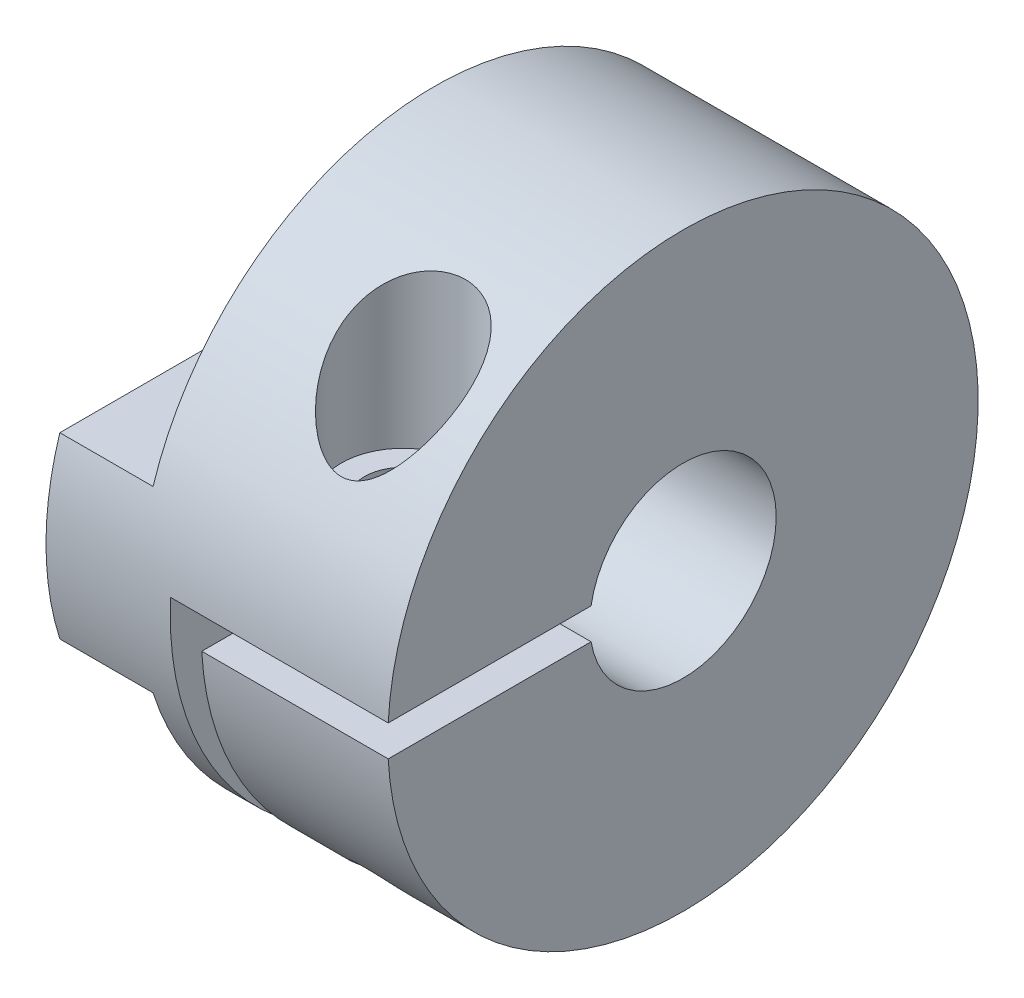
SolidWorks part; units mm, degrees
ref_plane "Plan1" through (0, 0, 0) normal (0, 0, 1) x (1, 0, 0)
ref_plane "Plan2" through (0, 0, 0) normal (0, 1, 0) x (1, 0, 0)
ref_plane "Plan3" through (0, 0, 0) normal (1, 0, 0) x (0, 0, -1)
sketch "Esquisse1" plane through (0, 0, 0) normal (0, 0, 1) x (1, 0, 0)
  line L0 (0, 0) -> (24.7291, 0) construction
  line L1 (0, 1.5) -> (0, 9.5)
  line L2 (0, 9.5) -> (11, 9.5)
  line L3 (11, 9.5) -> (11, 3)
  line L4 (11, 3) -> (4, 3)
  line L5 (4, 3) -> (4, 1.5)
  line L6 (4, 1.5) -> (0, 1.5)
  dimension "D1" = 9.5
  dimension "D2" = 3
  dimension "D3" = 11
  dimension "D4" = 1.5
  dimension "D5" = 7
revolve "Base-Révolution" add sketch "Esquisse1" angle 360 about L0
sketch "Esquisse2" plane through (0, 0, 0) normal (0, 0, 1) x (1, 0, 0)
  line L0 (-3.1407, 0) -> (12.8606, 0) construction
  line L1 (0, 0) -> (24.7291, 0) construction
  line L2 (0, 9.5) -> (0, -9.5) construction
  line L3 (0, 2.875) -> (3, 2.875)
  line L4 (0, 2.875) -> (0, 9.5)
  line L5 (0, 9.5) -> (3, 9.5)
  line L6 (3, 2.875) -> (3, 9.5)
  line L7 (11, 9.5) -> (0, 9.5) construction
  line L8 (3, -2.875) -> (3, -9.5)
  line L9 (0, -9.5) -> (3, -9.5)
  line L10 (0, -2.875) -> (0, -9.5)
  line L11 (0, -2.875) -> (3, -2.875)
  dimension "D1" = 3
  dimension "D2" = 2.875
extrude "Enlèv. mat.-Extru.1" cut sketch "Esquisse2" against normal mid plane 20
sketch "Esquisse3" plane through (0, 0, 0) normal (0, 1, 0) x (1, 0, 0)
  line L0 (11, 9.5) -> (0, 9.5) construction
  line L1 (4, -9.5) -> (5, -9.5)
  line L2 (4, -9.5) -> (4, 9.5)
  line L3 (4, 9.5) -> (5, 9.5)
  line L4 (5, -9.5) -> (5, 9.5)
  line L5 (3, 9.0545) -> (3, -9.0545) construction
  line L6 (0, -9.5) -> (11, -9.5) construction
  dimension "D1" = 1
  dimension "D2" = 1
extrude "Enlèv. mat.-Extru.2" cut sketch "Esquisse3" against normal through all
sketch "Esquisse4" plane through (11, 0, 0) normal (1, 0, 0) x (0, 0, -1)
  line L0 (0, 0) -> (-11.0166, 0) construction
  line L1 (-9.5, 0.5) -> (0, 0.5)
  line L2 (-9.5, 0.5) -> (-9.5, -0.5)
  line L3 (-9.5, -0.5) -> (0, -0.5)
  line L4 (0, 0.5) -> (0, -0.5)
  circle A0 centre (0, 0) radius 9.5 construction
  dimension "D1" = 1
extrude "Enlèv. mat.-Extru.3" cut sketch "Esquisse4" against normal blind 7
sketch "Esquisse5" plane through (0, 0, 0) normal (0, 1, 0) x (1, 0, 0)
  line L0 (11, -9.4868) -> (11, 9.5) construction
  line L1 (0, 0) -> (11.9937, 0) construction
  line L2 (0, 0) -> (24.7291, 0) construction
  circle A0 centre (8, -6) radius 1.25
  dimension "D1" = 2.5
  dimension "D2" = 3
  dimension "D3" = 6
extrude "Enlèv. mat.-Extru.4" cut sketch "Esquisse5" against normal mid plane 20
ref_plane "Plan4" through (0, 3.5, 0) normal (0, -1, 0) x (1, 0, 0)
sketch "Esquisse7" plane through (0, 3.5, 0) normal (0, -1, 0) x (1, 0, 0)
  circle A0 centre (8, 6) radius 2
  circle A1 centre (8, 6) radius 1.25 construction
  dimension "D1" = 4
extrude "Enlèv. mat.-Extru.6" cut sketch "Esquisse7" against normal up to next
